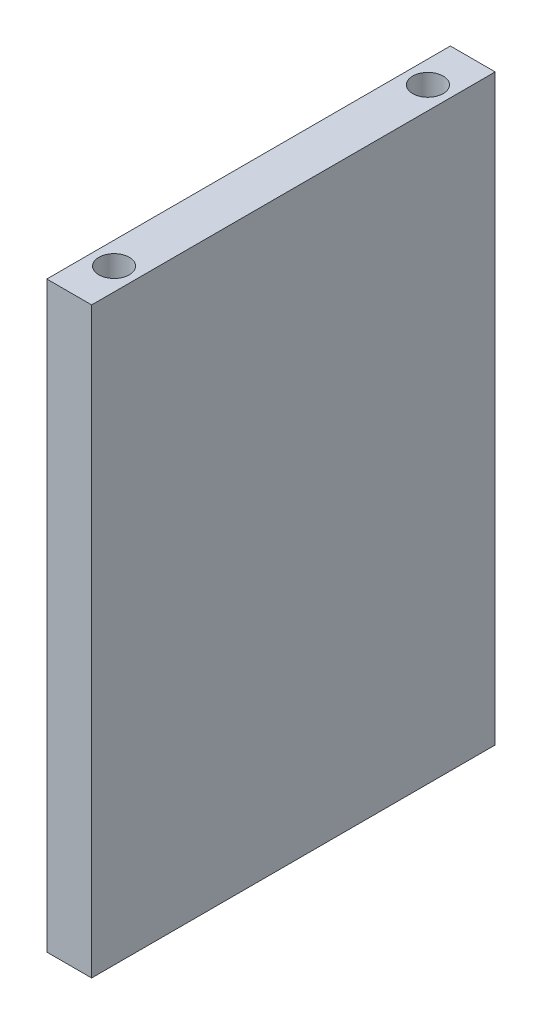
SolidWorks part; units mm, degrees
ref_plane "Front Plane" through (0, 0, 0) normal (0, 0, 1) x (1, 0, 0)
ref_plane "Top Plane" through (0, 0, 0) normal (0, 1, 0) x (1, 0, 0)
ref_plane "Right Plane" through (0, 0, 0) normal (1, 0, 0) x (0, 0, -1)
sketch "Sketch1" plane through (0, 0, 0) normal (0, 1, 0) x (1, 0, 0)
  line L1 (0, 0) -> (5, 0)
  line L2 (0, 0) -> (0, 45)
  line L3 (0, 45) -> (5, 45)
  line L4 (5, 0) -> (5, 45)
  dimension "D1" = 45
  dimension "D2" = 5
extrude "Boss-Extrude1" add sketch "Sketch1" along normal blind 65
hole_wizard "M3 Clearance Hole1" positions "Sketch3" profile "Sketch2" hole size "M3" standard "ANSI Metric"
sketch "Sketch3" plane through (0, 65, 0) normal (0, 1, 0) x (1, 0, 0)
  line L0 (5, 45) -> (0, 45) construction
  line L1 (0, 0) -> (5, 0) construction
  line L2 (5, 0) -> (5, 45) construction
  line L3 (0, 45) -> (0, 0) construction
  point P0 (2.5, 40)
  point P2 (2.5, 5)
  point P5 (2.5, 45)
  dimension "D1" = 35
  dimension "D2" = 5
  dimension "D3" = 5
  dimension "D4" = 2.5
  dimension "D5" = 2.5
sketch "Sketch2" plane through (2.5, 65, -40) normal (1, 0, 0) x (0, 0, 1)
  line L0 (0, 0) -> (0, 8.0215)
  line L1 (0, 8.0215) -> (1.7, 7)
  line L2 (1.7, 7) -> (1.7, 0)
  line L5 (1.7, 0) -> (0, 0)
  line L10 (0, 8.0215) -> (-1.7, 7) construction
  line L11 (0, -6.35) -> (0, 107.95) construction
  dimension "Hole Dia." = 3.4
  dimension "Hole Depth" = 7
  dimension "Drill Angle" = 118
hole_wizard "M3 Clearance Hole2" positions "Sketch5" profile "Sketch4" hole size "M3" standard "ANSI Metric"
sketch "Sketch5" plane through (0, 0, 0) normal (0, -1, 0) x (-1, 0, 0)
  line L1 (-5, 45) -> (0, 45) construction
  line L2 (-5, 0) -> (-5, 45) construction
  line L3 (0, 45) -> (0, 0) construction
  line L4 (0, 0) -> (-5, 0) construction
  point P0 (-2.5, 39.9997)
  point P2 (-2.5, 4.9997)
  point P18 (-23.3417, 11.8824)
  dimension "D1" = 2.5
  dimension "D2" = 35
  dimension "D3" = 5.0003
  dimension "D4" = 2.5
  dimension "D5" = 2.5
  dimension "D6" = 4.9997
  dimension "D7" = 2.5
sketch "Sketch4" plane through (2.5, 0, -39.9997) normal (1, 0, 0) x (0, 0, -1)
  line L0 (0, 0) -> (0, 8.0215)
  line L1 (0, 8.0215) -> (1.7, 7)
  line L2 (1.7, 7) -> (1.7, 0)
  line L5 (1.7, 0) -> (0, 0)
  line L10 (0, 8.0215) -> (-1.7, 7) construction
  line L11 (0, -6.35) -> (0, 107.95) construction
  dimension "Hole Dia." = 3.4
  dimension "Hole Depth" = 7
  dimension "Drill Angle" = 118
